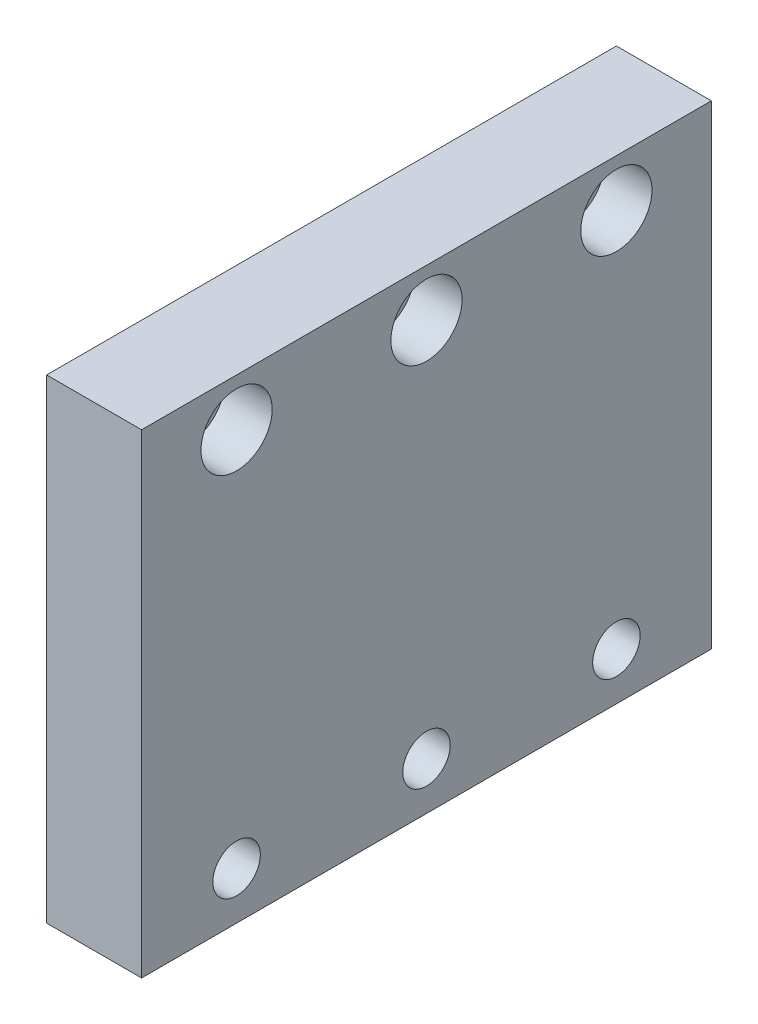
SolidWorks part; units mm, degrees
material "6061 Alloy"
ref_plane "Front" through (0, 0, 0) normal (0, 0, 1) x (1, 0, 0)
ref_plane "Top" through (0, 0, 0) normal (0, 1, 0) x (1, 0, 0)
ref_plane "Right" through (0, 0, 0) normal (1, 0, 0) x (0, 0, -1)
sketch "Sketch2" plane through (0, 0, 0) normal (0, 0, 1) x (1, 0, 0)
  line L7 (-6.35, 31.75) -> (6.35, 31.75)
  line L9 (6.35, -19.05) -> (6.35, -31.75)
  line L10 (6.35, 31.75) -> (6.35, -19.05)
  line L11 (-6.35, 31.75) -> (-6.35, 19.05)
  line L14 (-6.35, 19.05) -> (-6.35, -31.75)
  line L15 (-6.35, -31.75) -> (6.35, -31.75)
  dimension "D1" = 12.7
  dimension "D2" = 63.5
  dimension "D3" = 12.7
  dimension "D4" = 12.7
  dimension "D5" = 31.75
  dimension "D6" = 6.35
extrude "Boss-Extrude1" add sketch "Sketch2" along normal mid plane 76.2
hole_wizard "1/4\"-20 threaded c-bore" positions "Sketch4" profile "Sketch5" counterbore size "#10" standard "ANSI Inch" end condition through all
sketch "Sketch4" plane through (-6.35, 0, 0) normal (-1, 0, 0) x (0, 0, 1)
  line L0 (38.1, -31.75) -> (-38.1, -31.75) construction
  point P0 (-25.4, -25.4)
  point P2 (0, -25.4)
  point P4 (25.4, -25.4)
  point P10 (0, -31.75)
  dimension "D1" = 25.4
  dimension "D2" = 25.4
  dimension "D3" = 6.35
sketch "Sketch5" plane through (-6.35, -25.4, -25.4) normal (0, 1, 0) x (0, 0, 1)
  line L0 (0, 0) -> (0, 12.7)
  line L1 (0, 12.7) -> (3.175, 12.7)
  line L3 (3.175, 12.7) -> (3.175, 6.35)
  line L4 (3.175, 6.35) -> (4.7625, 6.35)
  line L5 (4.7625, 6.35) -> (4.7625, 0)
  line L7 (4.7625, 0) -> (0, 0)
  line L11 (0, -6.35) -> (0, 107.95) construction
  dimension "Thru Hole Dia." = 6.35
  dimension "Thru Hole Depth" = 12.7
  dimension "C'Bore Dia." = 9.525
  dimension "C'Bore Depth" = 6.35
hole_wizard "1/4\"-20 threaded c-bore opposite" positions "Sketch7" profile "Sketch6" counterbore size "#10" standard "ANSI Inch" end condition through all
sketch "Sketch7" plane through (6.35, 0, 0) normal (1, 0, 0) x (0, 0, -1)
  line L0 (-38.1, 31.75) -> (38.1, 31.75) construction
  point P0 (-25.4, 25.4)
  point P2 (0, 25.4)
  point P4 (25.4, 25.4)
  dimension "D1" = 6.35
  dimension "D2" = 25.4
  dimension "D3" = 25.4
sketch "Sketch6" plane through (6.35, 25.4, 25.4) normal (0, 1, 0) x (0, 0, -1)
  line L0 (0, 0) -> (0, 12.7)
  line L1 (0, 12.7) -> (3.175, 12.7)
  line L3 (3.175, 12.7) -> (3.175, 6.35)
  line L4 (3.175, 6.35) -> (4.7625, 6.35)
  line L5 (4.7625, 6.35) -> (4.7625, 0)
  line L7 (4.7625, 0) -> (0, 0)
  line L11 (0, -6.35) -> (0, 107.95) construction
  dimension "Thru Hole Dia." = 6.35
  dimension "Thru Hole Depth" = 12.7
  dimension "C'Bore Dia." = 9.525
  dimension "C'Bore Depth" = 6.35
